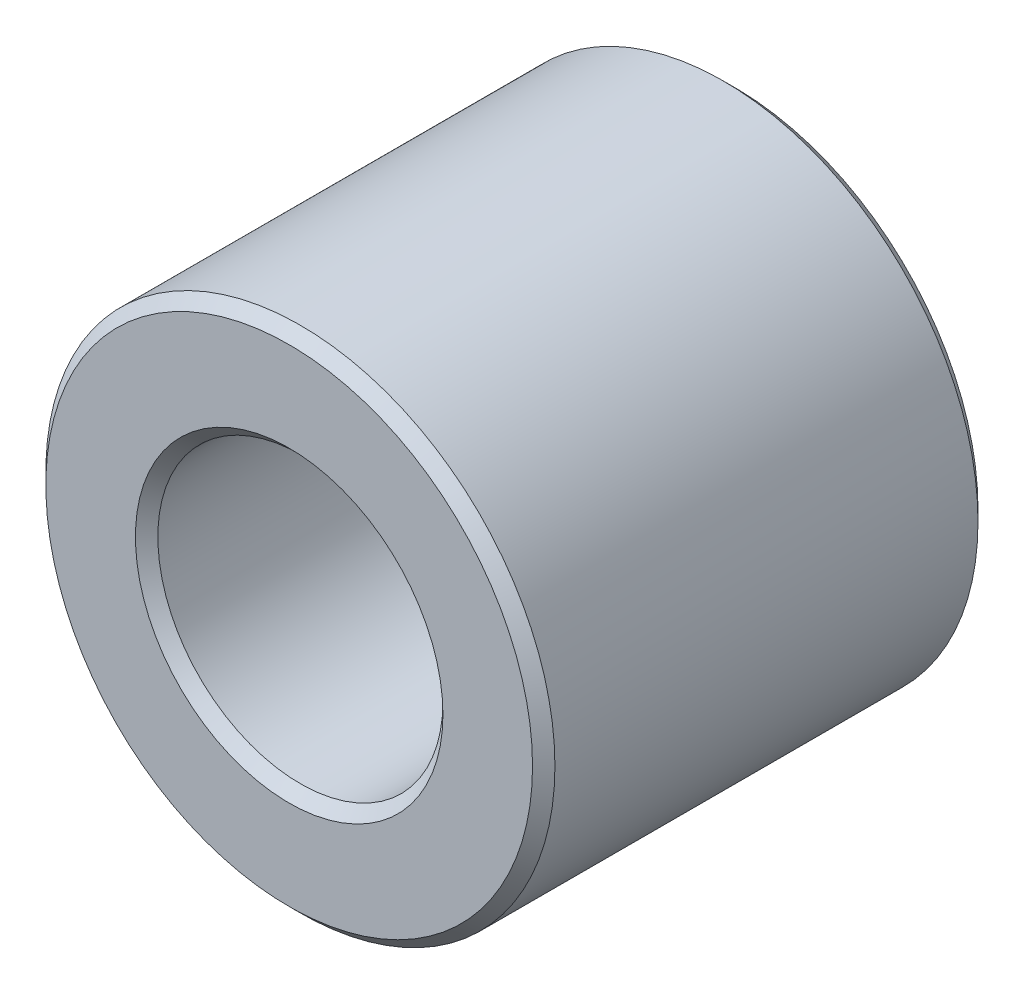
SolidWorks part; units mm, degrees
ref_plane "Front Plane" through (0, 0, 0) normal (0, 0, 1) x (1, 0, 0)
ref_plane "Top Plane" through (0, 0, 0) normal (0, 1, 0) x (1, 0, 0)
ref_plane "Right Plane" through (0, 0, 0) normal (1, 0, 0) x (0, 0, -1)
sketch "Sketch1" plane through (0, 0, 0) normal (0, 0, 1) x (1, 0, 0)
  circle A0 centre (0, 0) radius 3.175 construction
  circle A1 centre (0, 0) radius 1.778 construction
  point P4 (0, 3.175)
  dimension "ID" = 3.556
  dimension "OD" = 6.35
sketch "Sketch2" plane through (0, 0, 0) normal (1, 0, 0) x (0, 0, -1)
  line L0 (-2.7781, 3.175) -> (2.7781, 3.175) construction
  dimension "Length" = 5.5562
sketch "Sketch3" plane through (0, 0, 0) normal (0, 0, 1) x (1, 0, 0)
  circle A0 centre (0, 0) radius 1.778 construction
  circle A1 centre (0, 0) radius 3.175 construction
  circle A2 centre (0, 0) radius 1.778
  circle A3 centre (0, 0) radius 3.175
extrude "Boss-Extrude1" add sketch "Sketch3" against normal up to vertex (2.7781 mm away) and the other way up to vertex (2.7781 mm away) up to point (0, 3.175, -2.7781) other way up to point (0, 3.175, 2.7781)
chamfer "Chamfer1" distance 0.1397 angle 45 4 edges at (3.175, 0, 2.7781) (3.175, 0, -2.7781) (1.778, 0, 2.7781) (1.778, 0, -2.7781)
equation "\"D1@Chamfer1\"=(\"OD@Sketch1\"-\"ID@Sketch1\")*0.05"
